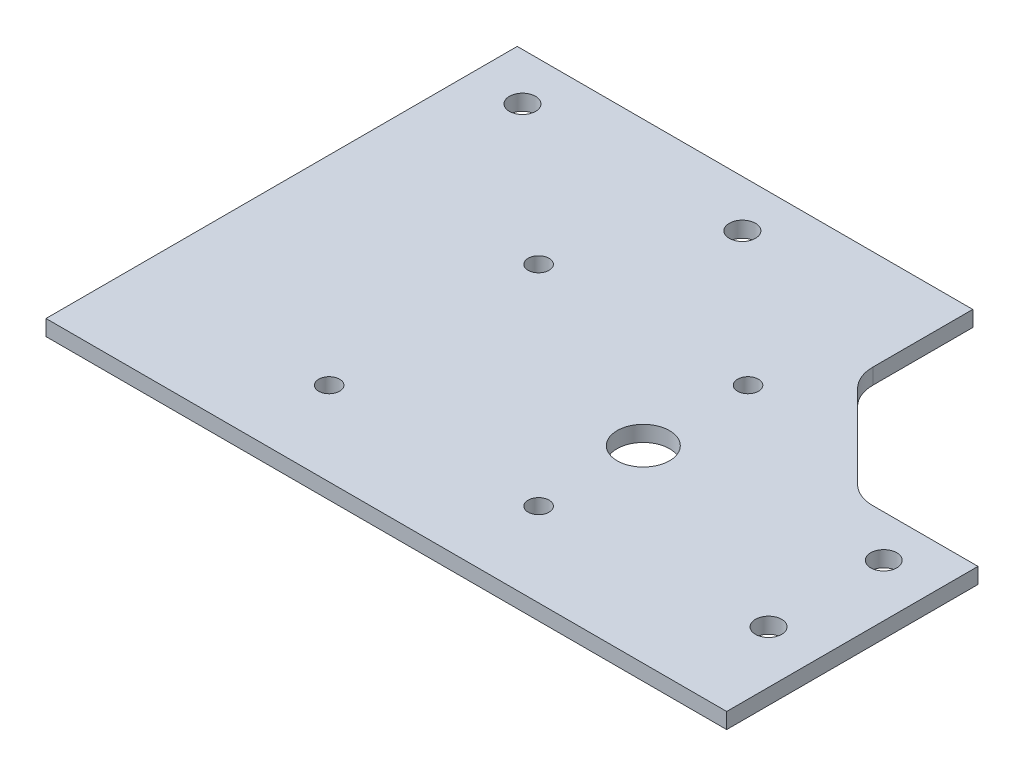
SolidWorks part; units mm, degrees
ref_plane "Front Plane" through (0, 0, 0) normal (0, 0, 1) x (1, 0, 0)
ref_plane "Top Plane" through (0, 0, 0) normal (0, 1, 0) x (1, 0, 0)
ref_plane "Right Plane" through (0, 0, 0) normal (1, 0, 0) x (0, 0, -1)
sketch "Sketch1" plane through (0, 0, 0) normal (0, 1, 0) x (1, 0, 0)
  line L0 (-383.3798, -208.6498) -> (-383.3798, -1044.376) construction
  line L1 (0, -42) -> (-20.1005, -42)
  line L2 (-130, 0) -> (-43, 0)
  line L3 (-130, 0) -> (-130, -90)
  line L4 (-130, -90) -> (0, -90)
  line L5 (0, -42) -> (0, -90)
  line L6 (-43, -19.1005) -> (-43, 0)
  line L7 (-40.9497, -24.0503) -> (-25.0503, -39.9497)
  line L8 (-143.2395, -24) -> (13.1519, -24) construction
  line L11 (-25, 5.43) -> (-25, -98.3175) construction
  arc A0 (-40.9497, -24.0503) -> (-43, -19.1005) centre (-36, -19.1005) cw
  arc A1 (-25.0503, -39.9497) -> (-20.1005, -42) centre (-20.1005, -35) ccw
  circle A7 centre (-78, -9) radius 2.5
  circle A8 centre (-120, -9) radius 2.5
  circle A9 centre (-10, -50) radius 2.5
  circle A10 centre (-10, -72) radius 2.5
  dimension "D17" = 9
  dimension "D18" = 10
  dimension "D20" = 18
  dimension "D5" = 7
  dimension "D6" = 7
  dimension "D13" = 130
  dimension "D14" = 90
  dimension "D19" = 52
  dimension "D21" = 10
  dimension "D22" = 40
sketch "Sketch2" plane through (0, 0, 0) normal (0, 1, 0) x (1, 0, 0)
  line L0 (-127.9195, -24) -> (-24.9195, -24) construction
  line L1 (-127.9195, -24) -> (-127.9195, -84) construction
  line L2 (-127.9195, -84) -> (-24.9195, -84) construction
  line L3 (-24.9195, -84) -> (-24.9195, -24) construction
  circle A0 centre (-51.9195, -74) radius 2
  circle A1 centre (-51.9195, -54) radius 5
  circle A2 centre (-51.9195, -34) radius 2
  circle A3 centre (-91.9195, -34) radius 2
  circle A4 centre (-91.9195, -74) radius 2
  dimension "D8" = 4
  dimension "D9" = 10
  dimension "D1" = 103
  dimension "D2" = 60
  dimension "D4" = 40
  dimension "D5" = 40
  dimension "D7" = 20
extrude "Boss-Extrude1" add sketch "Sketch1" along normal blind 3
extrude "Cut-Extrude2" cut sketch "Sketch2" along normal blind 3
